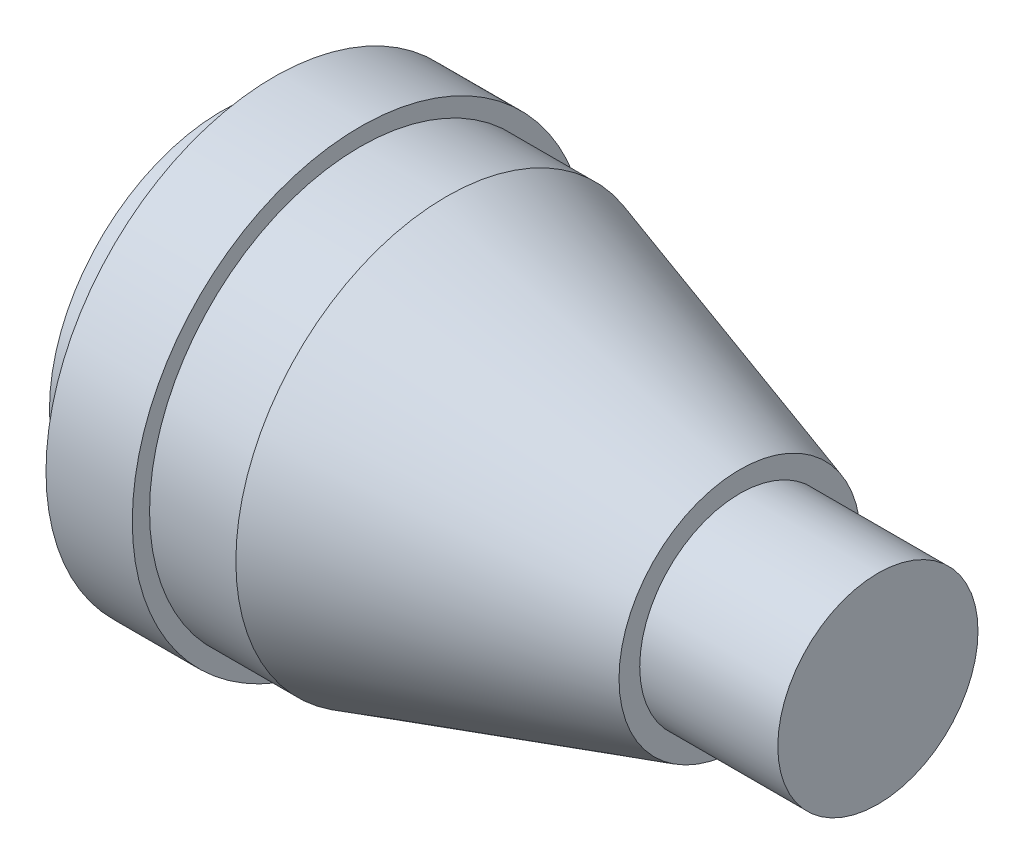
SolidWorks part; units mm, degrees
material "塑钢"
ref_plane "前视" through (0, 0, 0) normal (0, 0, 1) x (1, 0, 0)
ref_plane "上视" through (0, 0, 0) normal (0, 1, 0) x (1, 0, 0)
ref_plane "右视" through (0, 0, 0) normal (1, 0, 0) x (0, 0, -1)
sketch "草图1" plane through (0, 0, 0) normal (0, 0, 1) x (1, 0, 0)
  line L0 (0, 0) -> (197.386, 0) construction
  line L1 (0, 0) -> (0, 10)
  line L2 (0, 10) -> (3, 10)
  line L3 (3, 10) -> (3, 13.2)
  line L4 (3, 13.2) -> (8, 13.2)
  line L5 (8, 13.2) -> (8, 12.2)
  line L6 (8, 12.2) -> (13, 12.2)
  line L7 (13, 12.2) -> (30, 7)
  line L8 (30, 7) -> (30, 5.8)
  line L9 (30, 5.8) -> (38, 5.8)
  line L10 (38, 5.8) -> (38, 0)
  line L11 (38, 0) -> (0, 0)
  dimension "D1" = 26.4
  dimension "D2" = 20
  dimension "D3" = 3
  dimension "D4" = 30
  dimension "D5" = 11.6
  dimension "D6" = 1
  dimension "D7" = 5
  dimension "D8" = 8
  dimension "D9" = 5
  dimension "D10" = 14
revolve "旋转1" add sketch "草图1" angle 360 about L0
